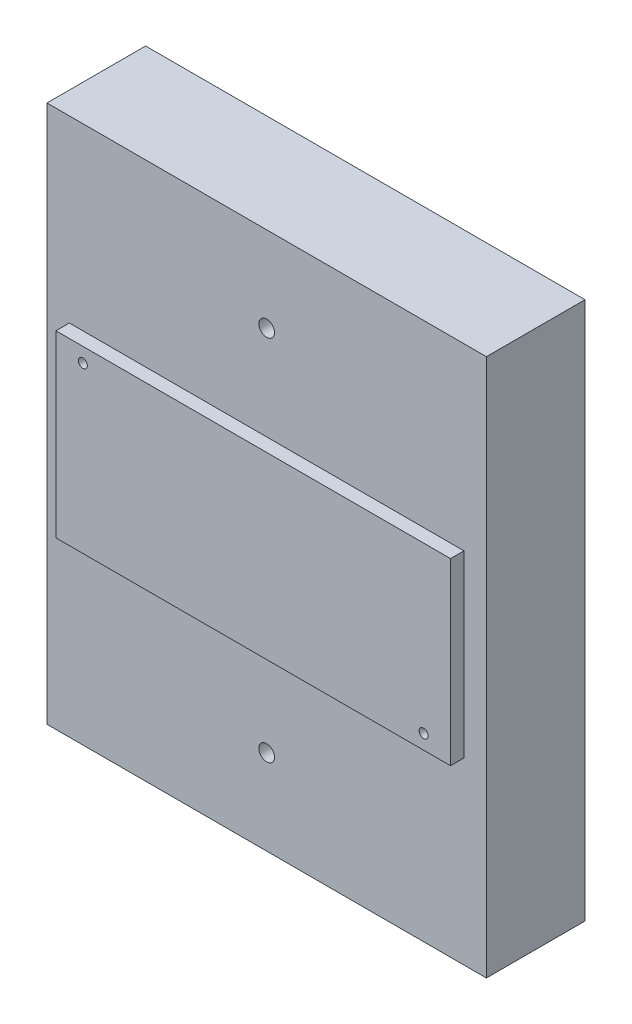
SolidWorks part; units mm, degrees
ref_plane "Front Plane" through (0, 0, 0) normal (0, 0, 1) x (1, 0, 0)
ref_plane "Top Plane" through (0, 0, 0) normal (0, 1, 0) x (1, 0, 0)
ref_plane "Right Plane" through (0, 0, 0) normal (1, 0, 0) x (0, 0, -1)
sketch "Sketch1" plane through (0, 0, 0) normal (0, 0, 1) x (1, 0, 0)
  line L0 (0, 60) -> (0, -60) construction
  line L5 (-49, 60) -> (49, 60)
  line L6 (-49, 60) -> (-49, -60)
  line L7 (-49, -60) -> (49, -60)
  line L8 (49, 60) -> (49, -60)
  line L9 (-49, 0) -> (49, 0) construction
  circle A0 centre (0, 41) radius 1.75
  circle A1 centre (0, -41) radius 1.75
  point P13 (0, 0)
  point P14 (0, 0)
  point P21 (0, 0)
  dimension "D2" = 3.5
  dimension "D1" = 82
  dimension "D3" = 98
  dimension "D4" = 120
extrude "Boss-Extrude1" add sketch "Sketch1" along normal blind 22
sketch "Sketch3" plane through (0, 0, 0) normal (0, 0, 1) x (1, 0, 0)
  line L0 (-44, -20) -> (-44, 20)
  line L1 (-44, -20) -> (44, -20)
  line L2 (44, -20) -> (44, 20)
  line L3 (-44, 20) -> (44, 20)
  line L4 (-44, 0) -> (44, 0) construction
  line L5 (0, 20) -> (0, -20) construction
  line L6 (-38, 16.75) -> (-38, 0) construction
  line L7 (38, -16.75) -> (38, 0) construction
  line L8 (-38, 16.75) -> (0, 16.75) construction
  line L9 (38, -16.75) -> (0, -16.75) construction
  circle A3 centre (-38, 16.75) radius 1
  circle A4 centre (38, -16.75) radius 1
  dimension "D5" = 2
  dimension "D1" = 88
  dimension "D2" = 40
  dimension "D3" = 76
  dimension "D4" = 33.5
extrude "Boss-Extrude2" add sketch "Sketch3" along normal blind 25
